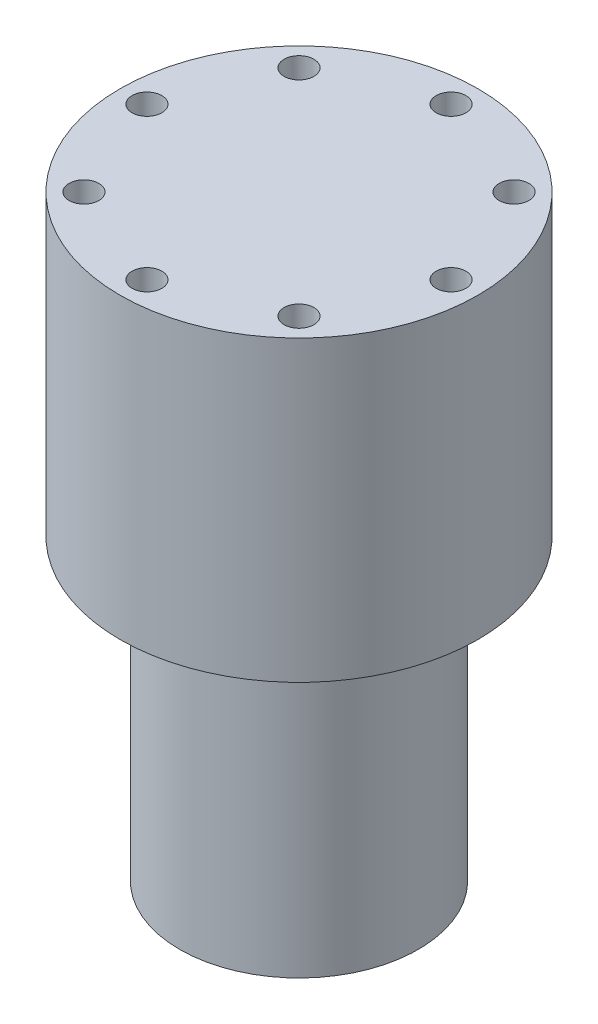
SolidWorks part; units mm, degrees
ref_plane "Front Plane" through (0, 0, 0) normal (0, 0, 1) x (1, 0, 0)
ref_plane "Top Plane" through (0, 0, 0) normal (0, 1, 0) x (1, 0, 0)
ref_plane "Right Plane" through (0, 0, 0) normal (1, 0, 0) x (0, 0, -1)
sketch "Sketch1" plane through (0, 0, 0) normal (0, 1, 0) x (1, 0, 0)
  circle A0 centre (0, 0) radius 25.4
extrude "Boss-Extrude1" add sketch "Sketch1" along normal blind 63.5
sketch "Sketch2" plane through (0, 63.5, 0) normal (0, 1, 0) x (1, 0, 0)
  circle A0 centre (0, 0) radius 38.1
extrude "Boss-Extrude2" add sketch "Sketch2" along normal blind 63.5
sketch "Sketch3" plane through (0, 127, 0) normal (0, 1, 0) x (1, 0, 0)
  circle A0 centre (0, 32.3772) radius 3.175
extrude "Cut-Extrude1" cut sketch "Sketch3" against normal blind 25.4
pattern_circular "CirPattern1" count 8 every 45 about axis through (0, 0, 0) along (0, 1, 0) of "Cut-Extrude1"
